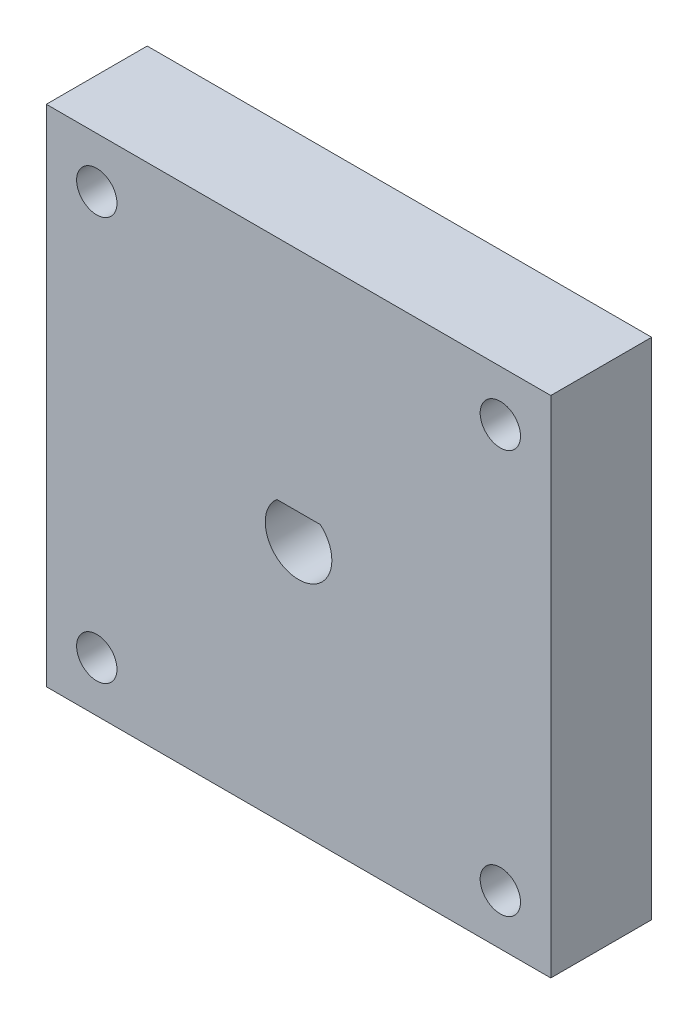
SolidWorks part; units mm, degrees
ref_plane "Ön Düzlem" through (0, 0, 0) normal (0, 0, 1) x (1, 0, 0)
ref_plane "Üst Düzlem" through (0, 0, 0) normal (0, 1, 0) x (1, 0, 0)
ref_plane "Sağ Düzlem" through (0, 0, 0) normal (1, 0, 0) x (0, 0, -1)
sketch "Çizim1" plane through (0, 0, 0) normal (0, 0, 1) x (1, 0, 0)
  line L0 (22.8459, 27.5) -> (27.1541, 27.5)
  line L1 (0, 0) -> (50, 0)
  line L2 (0, 0) -> (0, 50)
  line L3 (0, 50) -> (50, 50)
  line L4 (50, 0) -> (50, 50)
  arc A0 (22.8459, 27.5) -> (27.1541, 27.5) centre (25, 25) ccw
  circle A1 centre (5, 45) radius 2
  circle A2 centre (45, 45) radius 2
  circle A3 centre (45, 5) radius 2
  circle A4 centre (5, 5) radius 2
  dimension "D2" = 4
  dimension "D3" = 6.6
  dimension "D4" = 5
  dimension "D1" = 50
  dimension "D5" = 5
  dimension "D6" = 5
  dimension "D7" = 5
  dimension "D8" = 25
  dimension "D9" = 25
  dimension "D10" = 2.5
extrude "Yükseklik-Ekstrüzyon1" add sketch "Çizim1" along normal blind 10
